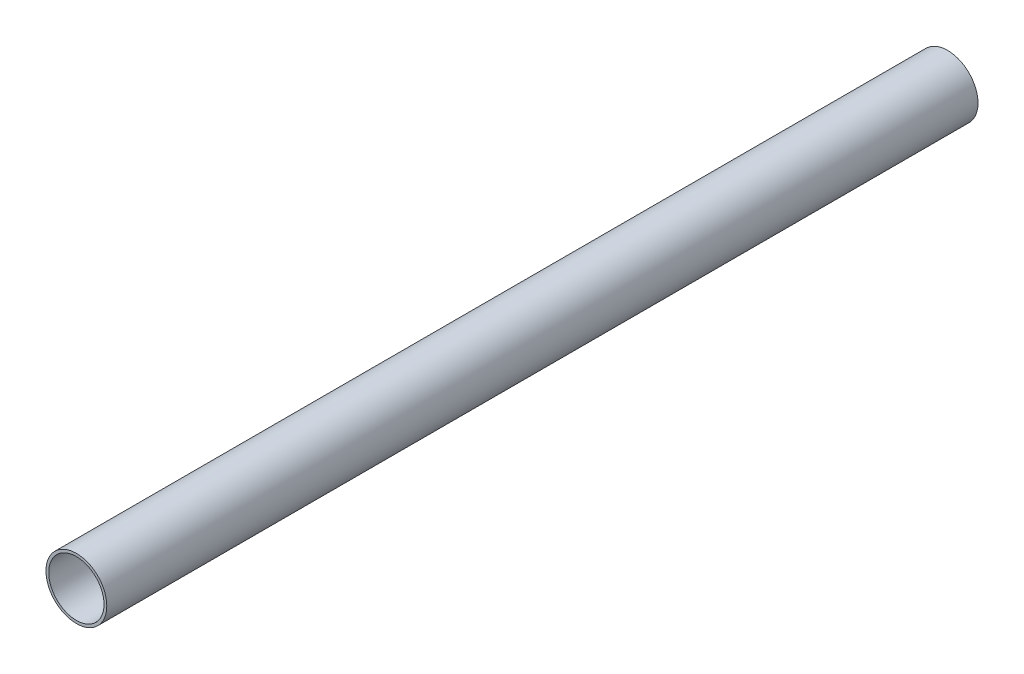
SolidWorks part; units mm, degrees
material "Thornel Mat VMA"
ref_plane "前视基准面" through (0, 0, 0) normal (0, 0, 1) x (1, 0, 0)
ref_plane "上视基准面" through (0, 0, 0) normal (0, 1, 0) x (1, 0, 0)
ref_plane "右视基准面" through (0, 0, 0) normal (1, 0, 0) x (0, 0, -1)
sketch "草图1" plane through (0, 0, 0) normal (0, 0, 1) x (1, 0, 0)
  circle A0 centre (0, 0) radius 11
  circle A1 centre (0, 0) radius 10
  dimension "D1" = 22
  dimension "D2" = 20
extrude "凸台-拉伸1" add sketch "草图1" along normal mid plane 315
